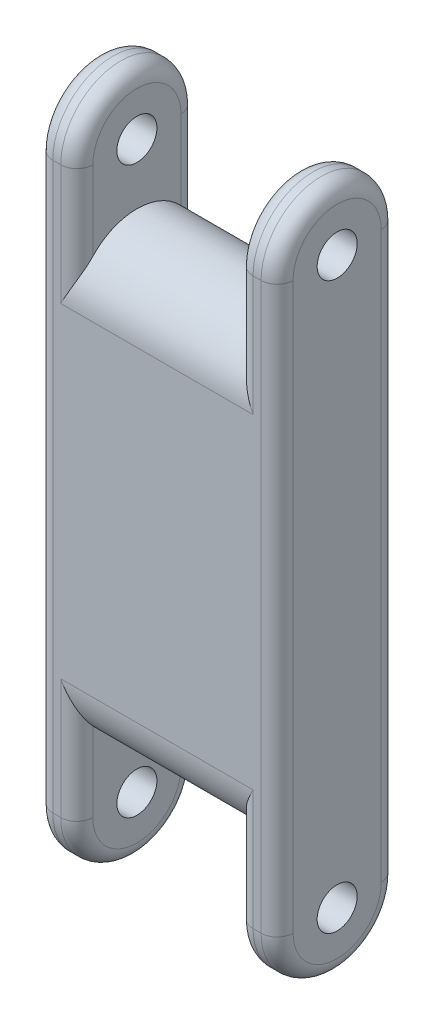
SolidWorks part; units mm, degrees
material "ABS"
ref_plane "Front" through (0, 0, 0) normal (0, 0, 1) x (1, 0, 0)
ref_plane "Top" through (0, 0, 0) normal (0, 1, 0) x (1, 0, 0)
ref_plane "Right" through (0, 0, 0) normal (1, 0, 0) x (0, 0, -1)
sketch "Sketch1" plane through (0, 0, 0) normal (1, 0, 0) x (0, 0, -1)
  line L0 (-4.7625, 0) -> (-4.7625, 44.8056)
  line L1 (4.7625, 44.8056) -> (4.7625, 0)
  arc A0 (-4.7625, 44.8056) -> (4.7625, 44.8056) centre (0, 44.8056) cw
  arc A1 (4.7625, 0) -> (-4.7625, 0) centre (0, 0) cw
  dimension "D1" = 9.525
  dimension "D2" = 44.8056
extrude "Boss-Extrude1" add sketch "Sketch1" along normal blind 19.05
sketch "Sketch2" plane through (19.05, 0, 0) normal (1, 0, 0) x (0, 0, -1)
  circle A0 centre (0, 0) radius 1.5875
  circle A1 centre (0, 44.8056) radius 1.5875
  dimension "D1" = 3.175
extrude "Cut-Extrude1" cut sketch "Sketch2" against normal blind 19.05
sketch3d "3DSketch1"
  line L0 (9.525, 44.8056, -4.7625) -> (9.525, 35.2806, -4.7625)
  line L1 (19.05, 44.8056, -4.7625) -> (0, 44.8056, -4.7625) construction
  line L2 (19.05, 44.8056, 4.7625) -> (0, 44.8056, 4.7625) construction
  line L3 (9.525, 44.8056, 4.7625) -> (9.525, 35.2806, 4.7625)
  line L5 (9.525, 0, 4.7625) -> (9.525, 9.525, 4.7625)
  line L7 (19.05, 0, 4.7625) -> (0, 0, 4.7625) construction
  line L8 (19.05, 0, -4.7625) -> (0, 0, -4.7625) construction
  line L9 (9.525, 0, -4.7625) -> (9.525, 9.525, -4.7625)
  arc A0 (9.525, 44.8056, -4.7625) -> (9.525, 44.8056, 4.7625) centre (9.525, 44.8056, 0) ccw
  arc A1 (9.525, 35.2806, -4.7625) -> (9.525, 35.2806, 4.7625) centre (9.525, 35.2806, 0) cw
  arc A2 (9.525, 0, 4.7625) -> (9.525, 0, -4.7625) centre (9.525, 0, 0) ccw
  arc A3 (9.525, 9.525, -4.7625) -> (9.525, 9.525, 4.7625) centre (9.525, 9.525, 0) cw
  point P6 (14.2875, 44.8056, 0)
  point P12 (14.2875, 35.2806, 0)
  point P18 (14.2875, 0, 0)
  point P24 (4.7625, 9.525, 0)
  dimension "D1" = 9.525
  dimension "D2" = 9.525
extrude "Cut-Extrude2" cut sketch "3DSketch1" along direction (-1, 0, 0) on the side against the normal mid plane 12.7
fillet "Fillet1" radius 1.27 20 edges at (0, 49.5681, 0) (0, 22.4028, -4.7625) (0, -4.7625, 0) (19.05, 49.5681, 0) (19.05, 22.4028, -4.7625) (19.05, -4.7625, 0) (0, 22.4028, 4.7625) (19.05, 22.4028, 4.7625)
sketch "Sketch3" plane through (0, 0, 0) normal (-1, 0, 0) x (0, 0, 1)
  line L0 (-3.4925, 44.8056) -> (-3.4925, 0) construction
  circle A0 centre (-2.0685, 42.4909) radius 1.3523
  circle A2 centre (0, 44.8056) radius 1.5875 construction
  dimension "D1" = 2.7047
  dimension "D2" = 1.424
  dimension "D3" = 2.3147
extrude "Boss-Extrude2" add sketch "Sketch3" along normal blind 2.54
fillet "Fillet2" radius 0.762 1 edges at (-2.54, 42.4909, -0.7161)
ref_plane "Plane1" through (0, 10.4032, 18.0189) normal (0, 0.5, 0.866) x (-1, 0, 0)
sketch "Sketch4" plane through (0, 10.4032, 18.0189) normal (0, 0.5, 0.866) x (-1, 0, 0)
  line L0 (0, -40.549) -> (0, -1.7462) construction
  line L2 (-1.905, -28.1726) -> (-17.145, -28.1726) construction
  circle A0 centre (0.8782, -37.9336) radius 0.6365
  dimension "D1" = 1.2731
  dimension "D2" = 0.8782
  dimension "D3" = 9.761
extrude "Cut-Extrude3" cut sketch "Sketch4" against normal through all
